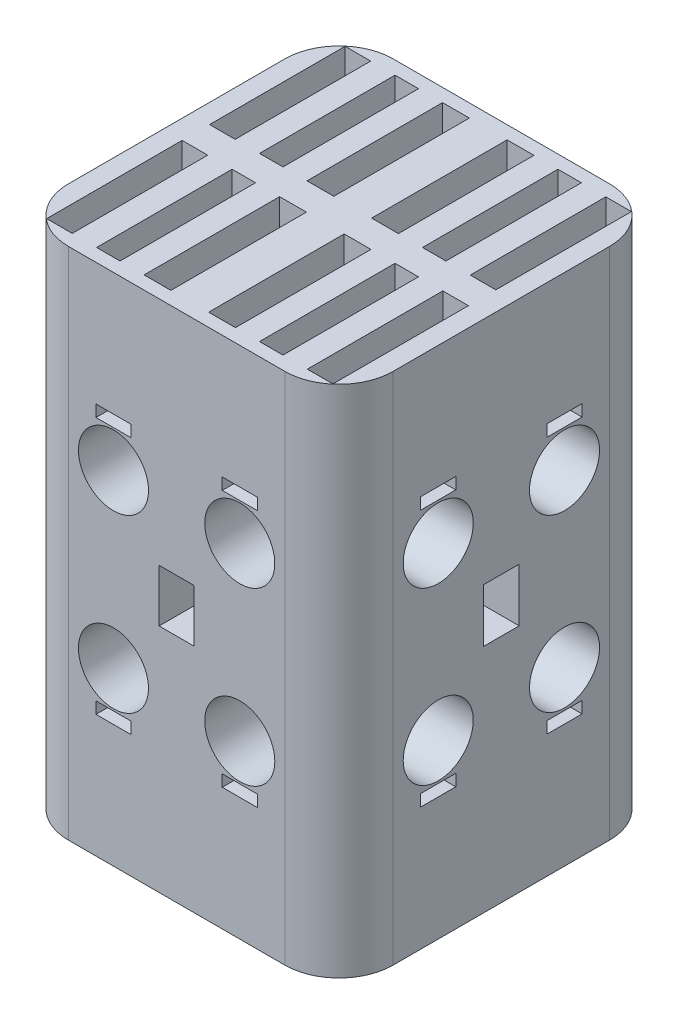
SolidWorks part; units mm, degrees
material "Plain Carbon Steel"
ref_plane "Front Plane" through (0, 0, 0) normal (0, 0, 1) x (1, 0, 0)
ref_plane "Top Plane" through (0, 0, 0) normal (0, 1, 0) x (1, 0, 0)
ref_plane "Right Plane" through (0, 0, 0) normal (1, 0, 0) x (0, 0, -1)
sketch "Sketch1" plane through (0, 0, 0) normal (0, 1, 0) x (1, 0, 0)
  line L1 (-20, 30) -> (20, 30)
  line L2 (-30, 20) -> (-30, -20)
  line L3 (-20, -30) -> (20, -30)
  line L4 (30, 20) -> (30, -20)
  line L5 (-30, 30) -> (30, -30) construction
  line L6 (-30, -30) -> (30, 30) construction
  arc A0 (20, 30) -> (30, 20) centre (20, 20) cw
  arc A1 (30, -20) -> (20, -30) centre (20, -20) cw
  arc A2 (-20, -30) -> (-30, -20) centre (-20, -20) cw
  arc A3 (-30, 20) -> (-20, 30) centre (-20, 20) cw
  point P0 (0, 0)
  dimension "D2" = 10
  dimension "D1" = 60
extrude "Boss-Extrude1" add sketch "Sketch1" along normal blind 95
sketch "Sketch2" plane through (0, 0, -30) normal (0, 0, -1) x (-1, 0, 0)
  line L0 (0, 95) -> (0, 0) construction
  line L1 (-20, 95) -> (20, 95) construction
  line L2 (30, 47.5) -> (-30, 47.5) construction
  line L3 (30, 95) -> (30, 0) construction
  line L4 (-30, 95) -> (-30, 0) construction
  line L5 (13.2363, 70.1712) -> (6.7637, 72.3288) construction
  line L6 (-13.2363, 72.3288) -> (-6.7637, 72.3288)
  line L7 (-13.2363, 72.3288) -> (-13.2363, 70.1712)
  line L8 (-13.2363, 70.1712) -> (-6.7637, 70.1712)
  line L9 (-6.7637, 72.3288) -> (-6.7637, 70.1712)
  line L10 (-13.2363, 72.3288) -> (-6.7637, 70.1712) construction
  line L11 (-13.2363, 70.1712) -> (-6.7637, 72.3288) construction
  line L12 (13.2363, 72.3288) -> (6.7637, 70.1712) construction
  line L13 (6.7637, 72.3288) -> (6.7637, 70.1712)
  line L14 (13.2363, 70.1712) -> (6.7637, 70.1712)
  line L15 (13.2363, 72.3288) -> (13.2363, 70.1712)
  line L16 (13.2363, 72.3288) -> (6.7637, 72.3288)
  line L17 (13.2363, 22.6712) -> (6.7637, 24.8288) construction
  line L18 (13.2363, 24.8288) -> (6.7637, 22.6712) construction
  line L19 (13.2363, 22.6712) -> (6.7637, 22.6712)
  line L20 (13.2363, 22.6712) -> (13.2363, 24.8288)
  line L21 (13.2363, 24.8288) -> (6.7637, 24.8288)
  line L22 (6.7637, 22.6712) -> (6.7637, 24.8288)
  line L23 (-13.2363, 24.8288) -> (-6.7637, 22.6712) construction
  line L24 (-13.2363, 22.6712) -> (-6.7637, 24.8288) construction
  line L25 (-6.7637, 22.6712) -> (-6.7637, 24.8288)
  line L26 (-13.2363, 24.8288) -> (-6.7637, 24.8288)
  line L27 (-13.2363, 22.6712) -> (-13.2363, 24.8288)
  line L28 (-13.2363, 22.6712) -> (-6.7637, 22.6712)
  line L30 (-3.2363, 52.3545) -> (3.2363, 52.3545)
  line L31 (-3.2363, 52.3545) -> (-3.2363, 42.6455)
  line L32 (-3.2363, 42.6455) -> (3.2363, 42.6455)
  line L33 (3.2363, 52.3545) -> (3.2363, 42.6455)
  line L34 (-3.2363, 52.3545) -> (3.2363, 42.6455) construction
  line L35 (-3.2363, 42.6455) -> (3.2363, 52.3545) construction
  circle A0 centre (-10, 63.3333) radius 6.4727
  circle A1 centre (10, 63.3333) radius 6.4727
  circle A2 centre (10, 31.6667) radius 6.4727
  circle A3 centre (-10, 31.6667) radius 6.4727
  point P13 (-10, 71.25)
  point P26 (10, 71.25)
  point P33 (10, 23.75)
  point P40 (-10, 23.75)
  point P41 (0, 47.5)
  dimension "D1" = 6.4727
  dimension "D2" = 15.8333
  dimension "D3" = 10
  dimension "D4" = 6.4727
  dimension "D5" = 2.1576
  dimension "D6" = 23.75
  dimension "D7" = 10
  dimension "D8" = 9.709
  dimension "D9" = 6.4727
sketch "Sketch3" plane through (30, 0, 0) normal (1, 0, 0) x (0, 0, -1)
  line L0 (0, 95.0764) -> (0, 0.0764) construction
  line L1 (35, 47.5764) -> (-35, 47.5764) construction
  line L2 (14.903, 70.2476) -> (8.4303, 72.4051) construction
  line L3 (-14.903, 72.4051) -> (-8.4303, 72.4051)
  line L4 (-14.903, 72.4051) -> (-14.903, 70.2476)
  line L5 (-14.903, 70.2476) -> (-8.4303, 70.2476)
  line L6 (-8.4303, 72.4051) -> (-8.4303, 70.2476)
  line L7 (-14.903, 72.4051) -> (-8.4303, 70.2476) construction
  line L8 (-14.903, 70.2476) -> (-8.4303, 72.4051) construction
  line L9 (14.903, 72.4051) -> (8.4303, 70.2476) construction
  line L10 (8.4303, 72.4051) -> (8.4303, 70.2476)
  line L11 (14.903, 70.2476) -> (8.4303, 70.2476)
  line L12 (14.903, 72.4051) -> (14.903, 70.2476)
  line L13 (14.903, 72.4051) -> (8.4303, 72.4051)
  line L14 (14.903, 22.7476) -> (8.4303, 24.9051) construction
  line L15 (14.903, 24.9051) -> (8.4303, 22.7476) construction
  line L16 (14.903, 22.7476) -> (8.4303, 22.7476)
  line L17 (14.903, 22.7476) -> (14.903, 24.9051)
  line L18 (14.903, 24.9051) -> (8.4303, 24.9051)
  line L19 (8.4303, 22.7476) -> (8.4303, 24.9051)
  line L20 (-14.903, 24.9051) -> (-8.4303, 22.7476) construction
  line L21 (-14.903, 22.7476) -> (-8.4303, 24.9051) construction
  line L22 (-8.4303, 22.7476) -> (-8.4303, 24.9051)
  line L23 (-14.903, 24.9051) -> (-8.4303, 24.9051)
  line L24 (-14.903, 22.7476) -> (-14.903, 24.9051)
  line L25 (-14.903, 22.7476) -> (-8.4303, 22.7476)
  line L26 (-3.2912, 52.5131) -> (3.2912, 52.5131)
  line L27 (-3.2912, 52.5131) -> (-3.2912, 42.6396)
  line L28 (-3.2912, 42.6396) -> (3.2912, 42.6396)
  line L29 (3.2912, 52.5131) -> (3.2912, 42.6396)
  line L30 (-3.2912, 52.5131) -> (3.2912, 42.6396) construction
  line L31 (-3.2912, 42.6396) -> (3.2912, 52.5131) construction
  circle A0 centre (-11.6667, 63.3546) radius 6.4727
  circle A1 centre (11.6667, 63.3546) radius 6.4727
  circle A2 centre (11.6667, 31.7981) radius 6.4727
  circle A3 centre (-11.6667, 31.7981) radius 6.4727
  point P0 (0, 0)
  point P8 (-11.6667, 71.3264)
  point P19 (11.6667, 71.3264)
  point P26 (11.6667, 23.8264)
  point P33 (-11.6667, 23.8264)
  point P34 (0, 47.5764)
sketch "Sketch4" plane through (0, 0, 30) normal (0, 0, 1) x (1, 0, 0)
  point P0 (0, 0)
extrude "Cut-Extrude1" cut sketch "Sketch3" against normal blind 10
sketch "Sketch5" plane through (0, 0, 30) normal (0, 0, 1) x (1, 0, 0)
  line L0 (0, 95) -> (0, 0) construction
  line L1 (35, 47.5) -> (-35, 47.5) construction
  line L2 (14.903, 70.1712) -> (8.4303, 72.3288) construction
  line L3 (-14.903, 72.3288) -> (-8.4303, 72.3288)
  line L4 (-14.903, 72.3288) -> (-14.903, 70.1712)
  line L5 (-14.903, 70.1712) -> (-8.4303, 70.1712)
  line L6 (-8.4303, 72.3288) -> (-8.4303, 70.1712)
  line L7 (-14.903, 72.3288) -> (-8.4303, 70.1712) construction
  line L8 (-14.903, 70.1712) -> (-8.4303, 72.3288) construction
  line L9 (14.903, 72.3288) -> (8.4303, 70.1712) construction
  line L10 (8.4303, 72.3288) -> (8.4303, 70.1712)
  line L11 (14.903, 70.1712) -> (8.4303, 70.1712)
  line L12 (14.903, 72.3288) -> (14.903, 70.1712)
  line L13 (14.903, 72.3288) -> (8.4303, 72.3288)
  line L14 (14.903, 22.6712) -> (8.4303, 24.8288) construction
  line L15 (14.903, 24.8288) -> (8.4303, 22.6712) construction
  line L16 (14.903, 22.6712) -> (8.4303, 22.6712)
  line L17 (14.903, 22.6712) -> (14.903, 24.8288)
  line L18 (14.903, 24.8288) -> (8.4303, 24.8288)
  line L19 (8.4303, 22.6712) -> (8.4303, 24.8288)
  line L20 (-14.903, 24.8288) -> (-8.4303, 22.6712) construction
  line L21 (-14.903, 22.6712) -> (-8.4303, 24.8288) construction
  line L22 (-8.4303, 22.6712) -> (-8.4303, 24.8288)
  line L23 (-14.903, 24.8288) -> (-8.4303, 24.8288)
  line L24 (-14.903, 22.6712) -> (-14.903, 24.8288)
  line L25 (-14.903, 22.6712) -> (-8.4303, 22.6712)
  line L26 (-3.2363, 52.3545) -> (3.2363, 52.3545)
  line L27 (-3.2363, 52.3545) -> (-3.2363, 42.6455)
  line L28 (-3.2363, 42.6455) -> (3.2363, 42.6455)
  line L29 (3.2363, 52.3545) -> (3.2363, 42.6455)
  line L30 (-3.2363, 52.3545) -> (3.2363, 42.6455) construction
  line L31 (-3.2363, 42.6455) -> (3.2363, 52.3545) construction
  circle A0 centre (-11.6667, 63.3333) radius 6.4727
  circle A1 centre (11.6667, 63.3333) radius 6.4727
  circle A2 centre (11.6667, 31.6667) radius 6.4727
  circle A3 centre (-11.6667, 31.6667) radius 6.4727
  point P0 (0, 47.5)
  point P8 (-11.6667, 71.25)
  point P19 (11.6667, 71.25)
  point P26 (11.6667, 23.75)
  point P33 (-11.6667, 23.75)
  point P34 (0, 47.5)
extrude "Cut-Extrude2" cut sketch "Sketch5" against normal blind 10
sketch "Sketch6" plane through (-30, 0, 0) normal (-1, 0, 0) x (0, 0, 1)
  line L0 (0, 0) -> (0, 95) construction
  line L1 (-20, 95) -> (20, 95) construction
  line L2 (30, 47.5) -> (-30, 47.5) construction
  line L3 (30, 95) -> (30, 0) construction
  line L4 (0, 94.9236) -> (0, -0.0764) construction
  line L5 (35, 47.4236) -> (-35, 47.4236) construction
  line L6 (14.903, 70.0949) -> (8.4303, 72.2524) construction
  line L7 (-14.903, 72.2524) -> (-8.4303, 72.2524)
  line L8 (-14.903, 72.2524) -> (-14.903, 70.0949)
  line L9 (-14.903, 70.0949) -> (-8.4303, 70.0949)
  line L10 (-8.4303, 72.2524) -> (-8.4303, 70.0949)
  line L11 (-14.903, 72.2524) -> (-8.4303, 70.0949) construction
  line L12 (-14.903, 70.0949) -> (-8.4303, 72.2524) construction
  line L13 (14.903, 72.2524) -> (8.4303, 70.0949) construction
  line L14 (8.4303, 72.2524) -> (8.4303, 70.0949)
  line L15 (14.903, 70.0949) -> (8.4303, 70.0949)
  line L16 (14.903, 72.2524) -> (14.903, 70.0949)
  line L17 (14.903, 72.2524) -> (8.4303, 72.2524)
  line L18 (14.903, 22.5949) -> (8.4303, 24.7524) construction
  line L19 (14.903, 24.7524) -> (8.4303, 22.5949) construction
  line L20 (14.903, 22.5949) -> (8.4303, 22.5949)
  line L21 (14.903, 22.5949) -> (14.903, 24.7524)
  line L22 (14.903, 24.7524) -> (8.4303, 24.7524)
  line L23 (8.4303, 22.5949) -> (8.4303, 24.7524)
  line L24 (-14.903, 24.7524) -> (-8.4303, 22.5949) construction
  line L25 (-14.903, 22.5949) -> (-8.4303, 24.7524) construction
  line L26 (-8.4303, 22.5949) -> (-8.4303, 24.7524)
  line L27 (-14.903, 24.7524) -> (-8.4303, 24.7524)
  line L28 (-14.903, 22.5949) -> (-14.903, 24.7524)
  line L29 (-14.903, 22.5949) -> (-8.4303, 22.5949)
  line L30 (-3.7689, 53.077) -> (3.7689, 53.077)
  line L31 (-3.7689, 53.077) -> (-3.7689, 41.7703)
  line L32 (-3.7689, 41.7703) -> (3.7689, 41.7703)
  line L33 (3.7689, 53.077) -> (3.7689, 41.7703)
  line L34 (-3.7689, 53.077) -> (3.7689, 41.7703) construction
  line L35 (-3.7689, 41.7703) -> (3.7689, 53.077) construction
  circle A0 centre (-11.6667, 63.257) radius 6.4727
  circle A1 centre (11.6667, 63.257) radius 6.4727
  circle A2 centre (11.6667, 31.5903) radius 6.4727
  circle A3 centre (-11.6667, 31.5903) radius 6.4727
  point P10 (0, 47.5)
  point P17 (-11.6667, 71.1736)
  point P28 (11.6667, 71.1736)
  point P35 (11.6667, 23.6736)
  point P42 (-11.6667, 23.6736)
  point P43 (0, 47.4236)
extrude "Cut-Extrude3" cut sketch "Sketch6" against normal blind 10
extrude "Cut-Extrude4" cut sketch "Sketch2" against normal blind 10
sketch "Sketch7" plane through (0, 95, 0) normal (0, 1, 0) x (1, 0, 0)
  line L0 (-30.1018, 0) -> (30.1018, 0)
  line L1 (-30.1018, 30.1018) -> (30.1018, 30.1018)
  line L2 (-30.1018, 30.1018) -> (-30.1018, -30.1018)
  line L3 (-30.1018, -30.1018) -> (30.1018, -30.1018)
  line L4 (30.1018, 30.1018) -> (30.1018, -30.1018)
  line L5 (-30.1018, 30.1018) -> (30.1018, -30.1018) construction
  line L6 (-30.1018, -30.1018) -> (30.1018, 30.1018) construction
  line L7 (0, 30.1018) -> (0, -30.1018)
  line L8 (-30.1018, 15.0509) -> (30.1018, 15.0509) construction
  line L9 (3.4884, -2.5319) -> (8.4398, -27.5699) construction
  line L10 (3.4884, 27.5699) -> (8.4398, 27.5699)
  line L11 (3.4884, 27.5699) -> (3.4884, 2.5319)
  line L12 (3.4884, 2.5319) -> (8.4398, 2.5319)
  line L13 (8.4398, 27.5699) -> (8.4398, 2.5319)
  line L14 (3.4884, 27.5699) -> (8.4398, 2.5319) construction
  line L15 (3.4884, 2.5319) -> (8.4398, 27.5699) construction
  line L16 (12.8847, 27.5699) -> (17.2171, 27.5699)
  line L17 (12.8847, 27.5699) -> (12.8847, 2.5319)
  line L18 (12.8847, 2.5319) -> (17.2171, 2.5319)
  line L19 (17.2171, 27.5699) -> (17.2171, 2.5319)
  line L20 (12.8847, 27.5699) -> (17.2171, 2.5319) construction
  line L21 (12.8847, 2.5319) -> (17.2171, 27.5699) construction
  line L22 (21.7183, 27.5699) -> (26.4446, 27.5699)
  line L23 (21.7183, 27.5699) -> (21.7183, 2.5319)
  line L24 (21.7183, 2.5319) -> (26.4446, 2.5319)
  line L25 (26.4446, 27.5699) -> (26.4446, 2.5319)
  line L26 (21.7183, 27.5699) -> (26.4446, 2.5319) construction
  line L27 (21.7183, 2.5319) -> (26.4446, 27.5699) construction
  line L28 (3.4884, -27.5699) -> (8.4398, -2.5319) construction
  line L29 (21.7183, -2.5319) -> (26.4446, -27.5699) construction
  line L30 (21.7183, -27.5699) -> (26.4446, -2.5319) construction
  line L31 (12.8847, -2.5319) -> (17.2171, -27.5699) construction
  line L32 (12.8847, -27.5699) -> (17.2171, -2.5319) construction
  line L33 (21.7183, -2.5319) -> (26.4446, -2.5319)
  line L34 (26.4446, -27.5699) -> (26.4446, -2.5319)
  line L35 (21.7183, -27.5699) -> (21.7183, -2.5319)
  line L36 (21.7183, -27.5699) -> (26.4446, -27.5699)
  line L37 (12.8847, -27.5699) -> (17.2171, -27.5699)
  line L38 (17.2171, -27.5699) -> (17.2171, -2.5319)
  line L39 (12.8847, -2.5319) -> (17.2171, -2.5319)
  line L40 (12.8847, -27.5699) -> (12.8847, -2.5319)
  line L41 (3.4884, -2.5319) -> (8.4398, -2.5319)
  line L42 (8.4398, -27.5699) -> (8.4398, -2.5319)
  line L43 (3.4884, -27.5699) -> (3.4884, -2.5319)
  line L44 (3.4884, -27.5699) -> (8.4398, -27.5699)
  line L45 (-21.7183, 2.5319) -> (-26.4446, 2.5319)
  line L46 (-21.7183, 27.5699) -> (-21.7183, 2.5319)
  line L47 (-21.7183, 27.5699) -> (-26.4446, 27.5699)
  line L48 (-26.4446, 27.5699) -> (-26.4446, 2.5319)
  line L49 (-21.7183, 2.5319) -> (-26.4446, 27.5699) construction
  line L50 (-21.7183, 27.5699) -> (-26.4446, 2.5319) construction
  line L51 (-12.8847, 2.5319) -> (-17.2171, 2.5319)
  line L52 (-17.2171, 27.5699) -> (-17.2171, 2.5319)
  line L53 (-12.8847, 27.5699) -> (-17.2171, 27.5699)
  line L54 (-12.8847, 2.5319) -> (-17.2171, 27.5699) construction
  line L55 (-12.8847, 27.5699) -> (-17.2171, 2.5319) construction
  line L56 (-12.8847, 27.5699) -> (-12.8847, 2.5319)
  line L57 (-3.4884, 2.5319) -> (-8.4398, 2.5319)
  line L58 (-3.4884, 2.5319) -> (-8.4398, 27.5699) construction
  line L59 (-8.4398, 27.5699) -> (-8.4398, 2.5319)
  line L60 (-3.4884, 27.5699) -> (-8.4398, 27.5699)
  line L61 (-3.4884, 27.5699) -> (-8.4398, 2.5319) construction
  line L62 (-3.4884, 27.5699) -> (-3.4884, 2.5319)
  line L63 (-21.7183, -27.5699) -> (-26.4446, -27.5699)
  line L64 (-26.4446, -27.5699) -> (-26.4446, -2.5319)
  line L65 (-21.7183, -27.5699) -> (-26.4446, -2.5319) construction
  line L66 (-21.7183, -2.5319) -> (-26.4446, -27.5699) construction
  line L67 (-21.7183, -27.5699) -> (-21.7183, -2.5319)
  line L68 (-21.7183, -2.5319) -> (-26.4446, -2.5319)
  line L69 (-12.8847, -2.5319) -> (-17.2171, -2.5319)
  line L70 (-12.8847, -27.5699) -> (-17.2171, -27.5699)
  line L71 (-17.2171, -27.5699) -> (-17.2171, -2.5319)
  line L72 (-12.8847, -2.5319) -> (-17.2171, -27.5699) construction
  line L73 (-12.8847, -27.5699) -> (-17.2171, -2.5319) construction
  line L74 (-12.8847, -27.5699) -> (-12.8847, -2.5319)
  line L75 (-3.4884, -27.5699) -> (-8.4398, -27.5699)
  line L76 (-8.4398, -27.5699) -> (-8.4398, -2.5319)
  line L77 (-3.4884, -27.5699) -> (-8.4398, -2.5319) construction
  line L78 (-3.4884, -2.5319) -> (-8.4398, -27.5699) construction
  line L79 (-3.4884, -27.5699) -> (-3.4884, -2.5319)
  line L80 (-3.4884, -2.5319) -> (-8.4398, -2.5319)
  point P0 (0, 0)
  point P12 (5.9641, 15.0509)
  point P17 (15.0509, 15.0509)
  point P22 (24.0815, 15.0509)
  dimension "D1" = 60.2036
  dimension "D2" = 15.0509
extrude "Cut-Extrude5" cut sketch "Sketch7" against normal blind 5 contours L47 L48 L45 L46 | L56 L53 L52 L51 | L62 L60 L59 L57 | L13 L10 L11 L12 | L19 L16 L17 L18 | L25 L22 L23 L24 | L35 L36 L34 L33 | L40 L37 L38 L39 | L43 L44 L42 L41 | L79 L80 L76 L75 | L70 L74 L69 L71 | L67 L68 L64 L63
sketch "Sketch11" plane through (0, 0, 20) normal (0, 0, 1) x (1, 0, 0)
  line L0 (0, 95) -> (0, 0) construction
  line L1 (-12.4815, 63.7408) -> (-10.8518, 63.7408)
  line L2 (-12.4815, 63.7408) -> (-12.4815, 62.9259)
  line L3 (-12.4815, 62.9259) -> (-10.8518, 62.9259)
  line L4 (-10.8518, 63.7408) -> (-10.8518, 62.9259)
  line L5 (-12.4815, 63.7408) -> (-10.8518, 62.9259) construction
  line L6 (-12.4815, 62.9259) -> (-10.8518, 63.7408) construction
  line L7 (-20, 95) -> (20, 95) construction
  line L8 (30, 47.5) -> (-30, 47.5) construction
  line L9 (30, 95) -> (30, 0) construction
  line L10 (-30, 95) -> (-30, 0) construction
  line L11 (10.8518, 63.7408) -> (10.8518, 62.9259)
  line L12 (12.4815, 62.9259) -> (10.8518, 62.9259)
  line L13 (12.4815, 62.9259) -> (10.8518, 63.7408) construction
  line L14 (12.4815, 63.7408) -> (10.8518, 62.9259) construction
  line L15 (12.4815, 63.7408) -> (12.4815, 62.9259)
  line L16 (12.4815, 63.7408) -> (10.8518, 63.7408)
  line L17 (12.4815, 31.2592) -> (12.4815, 32.0741)
  line L18 (12.4815, 32.0741) -> (10.8518, 32.0741)
  line L19 (10.8518, 31.2592) -> (10.8518, 32.0741)
  line L20 (12.4815, 31.2592) -> (10.8518, 31.2592)
  line L21 (12.4815, 31.2592) -> (10.8518, 32.0741) construction
  line L22 (12.4815, 32.0741) -> (10.8518, 31.2592) construction
  line L23 (-12.4815, 32.0741) -> (-10.8518, 32.0741)
  line L24 (-10.8518, 31.2592) -> (-10.8518, 32.0741)
  line L25 (-12.4815, 32.0741) -> (-10.8518, 31.2592) construction
  line L26 (-12.4815, 31.2592) -> (-10.8518, 32.0741) construction
  line L27 (-12.4815, 31.2592) -> (-10.8518, 31.2592)
  line L28 (-12.4815, 31.2592) -> (-12.4815, 32.0741)
  point P0 (-11.6667, 63.3333)
  point P1 (-11.6667, 63.3333)
  dimension "D1" = 1.6298
  dimension "D2" = 0.8149
extrude "Boss-Extrude3" add sketch "Sketch11" along normal blind 2
sketch "Sketch12" plane through (20, 0, 0) normal (1, 0, 0) x (0, 0, -1)
  line L0 (0, 95) -> (0, 0) construction
  line L1 (-20, 95) -> (20, 95) construction
  line L2 (30, 47.5) -> (-30, 47.5) construction
  line L3 (30, 95) -> (30, 0) construction
  line L4 (-30, 95) -> (-30, 0) construction
  line L5 (12.4815, 62.9471) -> (10.8518, 62.9471)
  line L6 (-12.4815, 63.762) -> (-10.8518, 63.762)
  line L7 (-12.4815, 63.762) -> (-12.4815, 62.9471)
  line L8 (-12.4815, 62.9471) -> (-10.8518, 62.9471)
  line L9 (-10.8518, 63.762) -> (-10.8518, 62.9471)
  line L10 (-12.4815, 63.762) -> (-10.8518, 62.9471) construction
  line L11 (-12.4815, 62.9471) -> (-10.8518, 63.762) construction
  line L12 (10.8518, 63.762) -> (10.8518, 62.9471)
  line L13 (12.4815, 62.9471) -> (10.8518, 63.762) construction
  line L14 (12.4815, 63.762) -> (10.8518, 62.9471) construction
  line L15 (12.4815, 63.762) -> (12.4815, 62.9471)
  line L16 (12.4815, 63.762) -> (10.8518, 63.762)
  line L17 (12.4815, 31.238) -> (12.4815, 32.0529)
  line L18 (12.4815, 32.0529) -> (10.8518, 32.0529)
  line L19 (12.4815, 31.238) -> (10.8518, 32.0529) construction
  line L20 (12.4815, 32.0529) -> (10.8518, 31.238) construction
  line L21 (10.8518, 31.238) -> (10.8518, 32.0529)
  line L22 (12.4815, 31.238) -> (10.8518, 31.238)
  line L23 (-12.4815, 32.0529) -> (-10.8518, 32.0529)
  line L24 (-10.8518, 31.238) -> (-10.8518, 32.0529)
  line L25 (-12.4815, 31.238) -> (-10.8518, 31.238)
  line L26 (-12.4815, 32.0529) -> (-10.8518, 31.238) construction
  line L27 (-12.4815, 31.238) -> (-10.8518, 32.0529) construction
  line L28 (-12.4815, 31.238) -> (-12.4815, 32.0529)
  point P0 (-11.6667, 63.3546)
  point P13 (-11.6667, 63.3546)
  dimension "D1" = 1.6298
  dimension "D2" = 0.8149
extrude "Boss-Extrude4" add sketch "Sketch12" along normal blind 2
sketch "Sketch13" plane through (0, 0, -20) normal (0, 0, -1) x (-1, 0, 0)
  line L0 (0, 95) -> (0, 0) construction
  line L1 (-20, 95) -> (20, 95) construction
  line L2 (30, 47.5) -> (-30, 47.5) construction
  line L3 (30, 95) -> (30, 0) construction
  line L4 (-30, 95) -> (-30, 0) construction
  line L5 (10.8149, 62.9259) -> (9.1851, 62.9259)
  line L6 (-10.8149, 63.7408) -> (-9.1851, 63.7408)
  line L7 (-10.8149, 63.7408) -> (-10.8149, 62.9259)
  line L8 (-10.8149, 62.9259) -> (-9.1851, 62.9259)
  line L9 (-9.1851, 63.7408) -> (-9.1851, 62.9259)
  line L10 (-10.8149, 63.7408) -> (-9.1851, 62.9259) construction
  line L11 (-10.8149, 62.9259) -> (-9.1851, 63.7408) construction
  line L12 (9.1851, 63.7408) -> (9.1851, 62.9259)
  line L13 (10.8149, 62.9259) -> (9.1851, 63.7408) construction
  line L14 (10.8149, 63.7408) -> (9.1851, 62.9259) construction
  line L15 (10.8149, 63.7408) -> (10.8149, 62.9259)
  line L16 (10.8149, 63.7408) -> (9.1851, 63.7408)
  line L17 (10.8149, 32.0741) -> (9.1851, 32.0741)
  line L18 (10.8149, 31.2592) -> (10.8149, 32.0741)
  line L19 (10.8149, 31.2592) -> (9.1851, 32.0741) construction
  line L20 (10.8149, 32.0741) -> (9.1851, 31.2592) construction
  line L21 (9.1851, 31.2592) -> (9.1851, 32.0741)
  line L22 (10.8149, 31.2592) -> (9.1851, 31.2592)
  line L23 (-10.8149, 32.0741) -> (-9.1851, 32.0741)
  line L24 (-9.1851, 31.2592) -> (-9.1851, 32.0741)
  line L25 (-10.8149, 31.2592) -> (-9.1851, 32.0741) construction
  line L26 (-10.8149, 32.0741) -> (-9.1851, 31.2592) construction
  line L27 (-10.8149, 31.2592) -> (-9.1851, 31.2592)
  line L28 (-10.8149, 31.2592) -> (-10.8149, 32.0741)
  point P0 (-10, 63.3333)
  point P13 (-10, 63.3333)
  dimension "D1" = 1.6298
  dimension "D2" = 0.8149
extrude "Boss-Extrude5" add sketch "Sketch13" along normal blind 2
sketch "Sketch14" plane through (-20, 0, 0) normal (-1, 0, 0) x (0, 0, 1)
  line L0 (0, 95) -> (0, 0) construction
  line L1 (-20, 95) -> (20, 95) construction
  line L2 (-30, 47.5) -> (30, 47.5) construction
  line L3 (-30, 95) -> (-30, 0) construction
  line L4 (30, 95) -> (30, 0) construction
  line L5 (12.4815, 62.8495) -> (10.8518, 62.8495)
  line L6 (-12.4815, 63.6644) -> (-10.8518, 63.6644)
  line L7 (-12.4815, 63.6644) -> (-12.4815, 62.8495)
  line L8 (-12.4815, 62.8495) -> (-10.8518, 62.8495)
  line L9 (-10.8518, 63.6644) -> (-10.8518, 62.8495)
  line L10 (-12.4815, 63.6644) -> (-10.8518, 62.8495) construction
  line L11 (-12.4815, 62.8495) -> (-10.8518, 63.6644) construction
  line L12 (10.8518, 63.6644) -> (10.8518, 62.8495)
  line L13 (12.4815, 62.8495) -> (10.8518, 63.6644) construction
  line L14 (12.4815, 63.6644) -> (10.8518, 62.8495) construction
  line L15 (12.4815, 63.6644) -> (12.4815, 62.8495)
  line L16 (12.4815, 63.6644) -> (10.8518, 63.6644)
  line L17 (12.4815, 31.3356) -> (12.4815, 32.1505)
  line L18 (12.4815, 32.1505) -> (10.8518, 32.1505)
  line L19 (12.4815, 31.3356) -> (10.8518, 32.1505) construction
  line L20 (12.4815, 32.1505) -> (10.8518, 31.3356) construction
  line L21 (10.8518, 31.3356) -> (10.8518, 32.1505)
  line L22 (12.4815, 31.3356) -> (10.8518, 31.3356)
  line L23 (-12.4815, 32.1505) -> (-10.8518, 32.1505)
  line L24 (-10.8518, 31.3356) -> (-10.8518, 32.1505)
  line L25 (-12.4815, 32.1505) -> (-10.8518, 31.3356) construction
  line L26 (-12.4815, 31.3356) -> (-10.8518, 32.1505) construction
  line L27 (-12.4815, 31.3356) -> (-10.8518, 31.3356)
  line L28 (-12.4815, 31.3356) -> (-12.4815, 32.1505)
  point P0 (-11.6667, 63.257)
  point P13 (-11.6667, 63.257)
  dimension "D1" = 1.6298
  dimension "D2" = 0.8149
extrude "Boss-Extrude6" add sketch "Sketch14" along normal blind 2
sketch "Sketch15" plane through (-20, 0, 0) normal (-1, 0, 0) x (0, 0, 1)
  line L0 (-30, 47.5) -> (30, 47.5) construction
  line L1 (-30, 95) -> (-30, 0) construction
  line L2 (30, 95) -> (30, 0) construction
  line L3 (0, 95) -> (0, 0) construction
  line L4 (-2.2285, 50.8428) -> (2.2285, 50.8428)
  line L5 (-2.2285, 50.8428) -> (-2.2285, 48.6143)
  line L6 (-2.2285, 48.6143) -> (2.2285, 48.6143)
  line L7 (2.2285, 50.8428) -> (2.2285, 48.6143)
  line L8 (-2.2285, 50.8428) -> (2.2285, 48.6143) construction
  line L9 (-2.2285, 48.6143) -> (2.2285, 50.8428) construction
  line L10 (-20, 95) -> (20, 95) construction
  circle A0 centre (-1.9146, 52.1229) radius 0.2021
  circle A1 centre (-0.6457, 52.1304) radius 0.2021
  circle A2 centre (0.6233, 52.138) radius 0.2021
  circle A3 centre (1.8922, 52.1455) radius 0.2021
  point P6 (0, 49.7285)
  dimension "D5" = 0.4041
  dimension "D1" = 4.4571
  dimension "D2" = 2.2285
  dimension "D3" = 2.2285
  dimension "D4" = 4
extrude "Boss-Extrude7" add sketch "Sketch15" along normal blind 2
sketch "Sketch16" plane through (0, 0, 20) normal (0, 0, 1) x (1, 0, 0)
  line L0 (0, 95) -> (0, 0) construction
  line L1 (-20, 95) -> (20, 95) construction
  line L2 (-30, 47.5) -> (30, 47.5) construction
  line L3 (-30, 95) -> (-30, 0) construction
  line L4 (30, 95) -> (30, 0) construction
  line L6 (-2.2285, 50.8428) -> (2.2285, 50.8428)
  line L7 (-2.2285, 50.8428) -> (-2.2285, 48.6143)
  line L8 (-2.2285, 48.6143) -> (2.2285, 48.6143)
  line L9 (2.2285, 50.8428) -> (2.2285, 48.6143)
  line L10 (-2.2285, 50.8428) -> (2.2285, 48.6143) construction
  line L11 (-2.2285, 48.6143) -> (2.2285, 50.8428) construction
  circle A0 centre (-1.9171, 51.5078) radius 0.2021
  circle A1 centre (-0.6583, 51.5032) radius 0.2021
  circle A2 centre (0.6004, 51.4985) radius 0.2021
  circle A3 centre (1.8592, 51.4939) radius 0.2021
  point P11 (0, 49.7285)
  point P16 (0, 47.5)
  dimension "D1" = 4.4571
  dimension "D2" = 2.2285
  dimension "D3" = 2.2285
  dimension "D4" = 0.4041
  dimension "D5" = 4
extrude "Boss-Extrude8" add sketch "Sketch16" along normal blind 2
sketch "Sketch18" plane through (20, 0, 0) normal (1, 0, 0) x (0, 0, -1)
  line L0 (0, 95) -> (0, 0) construction
  line L1 (-20, 95) -> (20, 95) construction
  line L2 (-30, 47.5) -> (30, 47.5) construction
  line L3 (-30, 95) -> (-30, 0) construction
  line L4 (30, 95) -> (30, 0) construction
  line L6 (-2.2285, 50.8428) -> (2.2285, 50.8428)
  line L7 (-2.2285, 50.8428) -> (-2.2285, 48.6143)
  line L8 (-2.2285, 48.6143) -> (2.2285, 48.6143)
  line L9 (2.2285, 50.8428) -> (2.2285, 48.6143)
  line L10 (-2.2285, 50.8428) -> (2.2285, 48.6143) construction
  line L11 (-2.2285, 48.6143) -> (2.2285, 50.8428) construction
  circle A0 centre (-1.8737, 51.6817) radius 0.2021
  circle A1 centre (-0.6273, 51.6818) radius 0.2021
  circle A2 centre (0.6192, 51.682) radius 0.2021
  circle A3 centre (1.8657, 51.6822) radius 0.2021
  point P11 (0, 49.7285)
  point P16 (0, 47.5)
  dimension "D1" = 4.4571
  dimension "D2" = 2.2285
  dimension "D3" = 2.2285
  dimension "D4" = 0.4041
  dimension "D5" = 4
extrude "Boss-Extrude9" add sketch "Sketch18" along normal blind 2
sketch "Sketch19" plane through (0, 0, -20) normal (0, 0, -1) x (-1, 0, 0)
  line L0 (0, 95) -> (0, 0) construction
  line L1 (-20, 95) -> (20, 95) construction
  line L2 (-30, 47.5) -> (30, 47.5) construction
  line L3 (-30, 95) -> (-30, 0) construction
  line L4 (30, 95) -> (30, 0) construction
  line L6 (-2.2285, 50.8428) -> (2.2285, 50.8428)
  line L7 (-2.2285, 50.8428) -> (-2.2285, 48.6143)
  line L8 (-2.2285, 48.6143) -> (2.2285, 48.6143)
  line L9 (2.2285, 50.8428) -> (2.2285, 48.6143)
  line L10 (-2.2285, 50.8428) -> (2.2285, 48.6143) construction
  line L11 (-2.2285, 48.6143) -> (2.2285, 50.8428) construction
  circle A0 centre (-1.8827, 51.4592) radius 0.2021
  circle A1 centre (-0.6178, 51.4656) radius 0.2021
  circle A2 centre (0.6471, 51.472) radius 0.2021
  circle A3 centre (1.912, 51.4784) radius 0.2021
  point P11 (0, 49.7285)
  point P16 (0, 47.5)
  dimension "D1" = 4.4571
  dimension "D2" = 2.2285
  dimension "D3" = 2.2285
  dimension "D4" = 0.4041
  dimension "D5" = 4
extrude "Boss-Extrude10" add sketch "Sketch19" along normal blind 2
sketch "Sketch20" plane through (0, 0, 0) normal (0, -1, 0) x (1, 0, 0)
  line L1 (-17.8383, 17.8383) -> (17.8383, 17.8383)
  line L2 (-17.8383, 17.8383) -> (-17.8383, -17.8383)
  line L3 (-17.8383, -17.8383) -> (17.8383, -17.8383)
  line L4 (17.8383, 17.8383) -> (17.8383, -17.8383)
  line L5 (-17.8383, 17.8383) -> (17.8383, -17.8383) construction
  line L6 (-17.8383, -17.8383) -> (17.8383, 17.8383) construction
  point P0 (0, 0)
extrude "Cut-Extrude6" cut sketch "Sketch20" against normal blind 84
equation "\"a\"=60"
equation "\"D1@Sketch1\"=\"a\""
equation "\"b\"=95"
equation "\"D1@Boss-Extrude1\"=\"b\""
equation "\"c\"=6.47269"
equation "\"D1@Sketch2\"=\"c\""
equation "\"D2@Sketch2\"=\"b\"/6"
equation "\"D3@Sketch2\"=\"a\"/6"
equation "\"D4@Sketch2\"=\"c\""
equation "\"D5@Sketch2\"=\"c\"/3"
equation "\"D6@Sketch2\"=\"b\"/4"
equation "\"D7@Sketch2\"=\"a\"/6"
equation "\"D8@Sketch2\"=\"c\"*1.5"
equation "\"D9@Sketch2\"=\"c\""
equation "\"d\"=60.2036"
equation "\"D1@Sketch7\"=\"d\""
equation "\"D2@Sketch7\"=\"d\"/4"
equation "\"e\"=1.62976"
equation "\"D1@Sketch11\"=\"e\""
equation "\"D2@Sketch11\"=\"e\"/2"
equation "\"D1@Sketch12\"=\"e\""
equation "\"D2@Sketch12\"=\"e\"/2"
equation "\"D1@Sketch13\"=\"e\""
equation "\"D2@Sketch13\"=\"e\"/2"
equation "\"D1@Sketch14\"=\"e\""
equation "\"D2@Sketch14\"=\"e\"/2"
equation "\"f\"=4.45706"
equation "\"D1@Sketch15\"=\"f\""
equation "\"D2@Sketch15\"=\"f\"/2"
equation "\"D3@Sketch15\"=\"f\"/2"
equation "\"D1@Sketch16\"=\"f\""
equation "\"D2@Sketch16\"=\"f\"/2"
equation "\"D3@Sketch16\"=\"f\"/2"
equation "\"g\"=0.404132"
equation "\"D5@Sketch15\"=\"g\""
equation "\"D4@Sketch16\"=\"g\""
equation "\"D1@Sketch18\"=\"f\""
equation "\"D2@Sketch18\"=\"f\"/2"
equation "\"D3@Sketch18\"=\"f\"/2"
equation "\"D4@Sketch18\"=\"g\""
equation "\"D1@Sketch19\"=\"f\""
equation "\"D2@Sketch19\"=\"f\"/2"
equation "\"D3@Sketch19\"=\"f\"/2"
equation "\"D4@Sketch19\"=\"g\""
